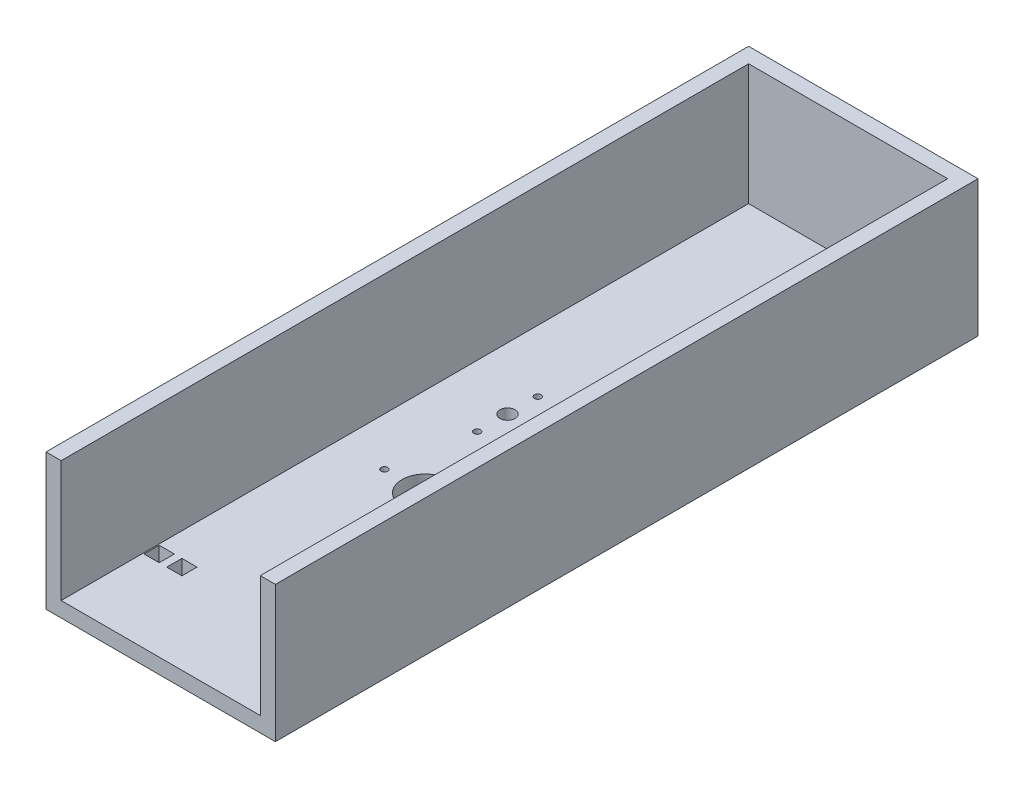
SolidWorks part; units mm, degrees
ref_plane "Front Plane" through (0, 0, 0) normal (0, 0, 1) x (1, 0, 0)
ref_plane "Top Plane" through (0, 0, 0) normal (0, 1, 0) x (1, 0, 0)
ref_plane "Right Plane" through (0, 0, 0) normal (1, 0, 0) x (0, 0, -1)
sketch "Sketch1" plane through (0, 0, 0) normal (0, 0, 1) x (1, 0, 0)
  line L0 (0, 0) -> (41.75, 0)
  line L1 (41.75, 0) -> (41.75, 22.225)
  line L2 (41.75, 50.8) -> (48.1, 50.8)
  line L3 (48.1, 50.8) -> (48.1, -6.35)
  line L4 (48.1, -6.35) -> (0, -6.35)
  line L5 (0, -6.35) -> (0, 0)
  line L6 (41.75, 22.225) -> (41.75, 50.8)
  dimension "D1" = 41.75
  dimension "D2" = 6.35
  dimension "D3" = 6.35
  dimension "D4" = 50.8
extrude "Boss-Extrude1" add sketch "Sketch1" along normal blind 294.64 contours L0 L1 L6 L2 L3 L4 L5
mirror "Mirror1" about plane through (0, -6.35, 294.64) normal (-1, 0, 0) of bodies 101
sketch "Sketch2" plane through (0, 0, 0) normal (0, 1, 0) x (1, 0, 0)
  line L0 (-41.75, -294.64) -> (-41.75, 0) construction
  line L1 (41.75, 0) -> (-41.75, 0)
  line L2 (41.75, 0) -> (41.75, -6.35)
  line L3 (41.75, -6.35) -> (-41.75, -6.35)
  line L4 (-41.75, 0) -> (-41.75, -6.35)
  dimension "D1" = 6.35
extrude "Boss-Extrude2" add sketch "Sketch2" along normal up to surface (50.8 mm away) up to face at (44.925, 50.8, 147.32)
sketch "Sketch3" plane through (0, -6.35, 0) normal (0, -1, 0) x (1, 0, 0)
  line L0 (48.1, 0) -> (-48.1, 0) construction
  line L1 (0, 12.7) -> (0, 0) construction
  line L2 (0, 93.98) -> (0, 12.7) construction
  circle A0 centre (0, 12.7) radius 2.3813
  circle A1 centre (0, 93.98) radius 2.3812
  dimension "D1" = 4.7625
  dimension "D2" = 4.7625
  dimension "D3" = 12.7
  dimension "D4" = 81.28
extrude "Cut-Extrude1" cut sketch "Sketch3" against normal up to surface (6.35 mm away) up to face at (0, 0, 150.495)
sketch "Sketch4" plane through (0, 0, 0) normal (0, 1, 0) x (1, 0, 0)
  line L0 (-41.75, -294.64) -> (41.75, -294.64) construction
  line L1 (41.75, -294.64) -> (41.75, -6.35) construction
  line L2 (4.4, -213.64) -> (-4.49, -179.2092) construction
  line L3 (4.4, -213.64) -> (-21.4508, -213.64) construction
  line L4 (-4.49, -179.2092) -> (-21.635, -179.2092) construction
  line L5 (-4.49, -179.2092) -> (12.655, -179.2092) construction
  circle A0 centre (-4.49, -179.2092) radius 9.7282
  circle A1 centre (-21.635, -179.2092) radius 1.3891
  circle A2 centre (12.655, -179.2092) radius 1.3891
  point P0 (4.4, -213.64)
  dimension "D5" = 19.4564
  dimension "D7" = 2.7781
  dimension "D8" = 2.7781
  dimension "D1" = 81
  dimension "D2" = 37.35
  dimension "D3" = 35.56
  dimension "D4" = 75.522
  dimension "D6" = 17.145
extrude "Cut-Extrude2" cut sketch "Sketch4" against normal up to next
sketch "Sketch5" plane through (0, 0, 0) normal (0, 1, 0) x (1, 0, 0)
  line L0 (41.75, -294.64) -> (41.75, -6.35) construction
  line L1 (-41.75, -294.64) -> (-41.75, -6.35) construction
  line L2 (-41.75, -6.35) -> (41.75, -6.35) construction
  line L3 (15.875, -133.35) -> (15.875, -146.05) construction
  line L4 (-41.75, -6.35) -> (41.75, -6.35) construction
  line L5 (15.875, -133.35) -> (15.875, -120.65) construction
  line L6 (-15.875, -120.65) -> (-15.875, -133.35) construction
  line L7 (-15.875, -133.35) -> (-15.875, -146.05) construction
  circle A0 centre (15.875, -133.35) radius 3.175
  circle A1 centre (-15.875, -133.35) radius 3.175
  circle A4 centre (15.875, -146.05) radius 1.3891
  circle A5 centre (15.875, -120.65) radius 1.3891
  circle A6 centre (-15.875, -146.05) radius 1.3891
  circle A7 centre (-15.875, -120.65) radius 1.3891
  dimension "D1" = 6.35
  dimension "D2" = 6.35
  dimension "D7" = 2.7781
  dimension "D8" = 2.7781
  dimension "D10" = 2.7781
  dimension "D11" = 2.7781
  dimension "D3" = 25.875
  dimension "D4" = 25.875
  dimension "D5" = 127
  dimension "D6" = 127
  dimension "D9" = 12.7
  dimension "D12" = 12.7
extrude "Cut-Extrude3" cut sketch "Sketch5" against normal up to next and the other way through all
sketch "Sketch6" plane through (0, 0, 0) normal (0, 1, 0) x (1, 0, 0)
  line L0 (25.4, -260.35) -> (-25.4, -260.35) construction
  line L1 (31.75, -260.35) -> (25.4, -260.35)
  line L2 (31.75, -260.35) -> (31.75, -254)
  line L3 (31.75, -254) -> (25.4, -254)
  line L4 (25.4, -260.35) -> (25.4, -254)
  line L5 (-25.4, -260.35) -> (-31.75, -260.35)
  line L6 (-25.4, -260.35) -> (-25.4, -254)
  line L7 (-25.4, -254) -> (-31.75, -254)
  line L8 (-31.75, -260.35) -> (-31.75, -254)
  line L9 (0, -260.35) -> (0, -6.35) construction
  line L11 (-41.75, -6.35) -> (41.75, -6.35) construction
  line L12 (34.925, -254) -> (-34.925, -254) construction
  line L13 (34.925, -260.35) -> (41.275, -260.35)
  line L14 (34.925, -260.35) -> (34.925, -254)
  line L15 (34.925, -254) -> (41.275, -254)
  line L16 (41.275, -260.35) -> (41.275, -254)
  line L17 (-34.925, -260.35) -> (-41.275, -260.35)
  line L18 (-34.925, -260.35) -> (-34.925, -254)
  line L19 (-34.925, -254) -> (-41.275, -254)
  line L20 (-41.275, -260.35) -> (-41.275, -254)
  line L21 (-41.75, -6.35) -> (41.75, -6.35) construction
  dimension "D1" = 57.15
  dimension "D2" = 6.35
  dimension "D3" = 6.35
  dimension "D4" = 254
  dimension "D5" = 3.175
  dimension "D6" = 3.175
  dimension "D7" = 247.65
extrude "Cut-Extrude4" cut sketch "Sketch6" against normal up to surface (6.35 mm away) up to face at (-14.4859, -6.35, 146.05)
sketch "Sketch7" plane through (0, -6.35, 0) normal (0, -1, 0) x (1, 0, 0)
  line B0 (-48.1, 0) -> (48.1, 0)
  line B1 (48.1, 0) -> (48.1, 294.64)
  line B2 (48.1, 294.64) -> (-48.1, 294.64)
  line B3 (-48.1, 294.64) -> (-48.1, 0)
  line B4 (41.275, 254) -> (34.925, 254)
  line B5 (41.275, 260.35) -> (41.275, 254)
  line B6 (34.925, 260.35) -> (41.275, 260.35)
  line B7 (34.925, 254) -> (34.925, 260.35)
  line B8 (31.75, 260.35) -> (31.75, 254)
  line B9 (25.4, 260.35) -> (31.75, 260.35)
  line B10 (25.4, 254) -> (25.4, 260.35)
  line B11 (31.75, 254) -> (25.4, 254)
  line B12 (-25.4, 254) -> (-31.75, 254)
  line B13 (-25.4, 260.35) -> (-25.4, 254)
  line B14 (-31.75, 260.35) -> (-25.4, 260.35)
  line B15 (-31.75, 254) -> (-31.75, 260.35)
  line B16 (-41.275, 254) -> (-41.275, 260.35)
  line B17 (-41.275, 260.35) -> (-34.925, 260.35)
  line B18 (-34.925, 260.35) -> (-34.925, 254)
  line B19 (-34.925, 254) -> (-41.275, 254)
  circle B20 centre (15.875, 120.65) radius 1.3891
  circle B21 centre (15.875, 133.35) radius 3.175
  circle B22 centre (15.875, 146.05) radius 1.3891
  circle B23 centre (-15.875, 146.05) radius 1.3891
  circle B24 centre (-15.875, 133.35) radius 3.175
  circle B25 centre (-15.875, 120.65) radius 1.3891
  circle B26 centre (12.655, 179.2092) radius 1.3891
  circle B27 centre (-21.635, 179.2092) radius 1.3891
  circle B28 centre (-4.49, 179.2092) radius 9.7282
sketch_block_instance "Block1-1"
sketch_block "Block1"
sketch "Sketch8" plane through (0, 0, 6.35) normal (0, 0, 1) x (1, 0, 0)
  line B0 (41.75, 50.8) -> (-41.75, 50.8)
  line B1 (-41.75, 50.8) -> (-41.75, 0)
  line B2 (-41.75, 0) -> (41.75, 0)
  line B3 (41.75, 0) -> (41.75, 50.8)
sketch_block_instance "Block2-1"
sketch_block "Block2"
